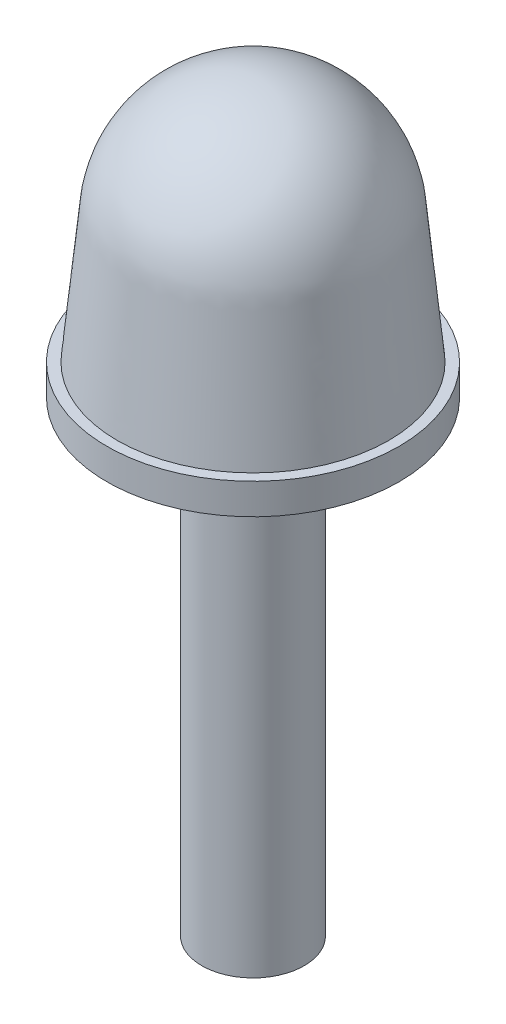
SolidWorks part; units mm, degrees
ref_plane "Front Plane" through (0, 0, 0) normal (0, 0, 1) x (1, 0, 0)
ref_plane "Top Plane" through (0, 0, 0) normal (0, 1, 0) x (1, 0, 0)
ref_plane "Right Plane" through (0, 0, 0) normal (1, 0, 0) x (0, 0, -1)
sketch "Sketch1" plane through (0, 0, 0) normal (0, 0, 1) x (1, 0, 0)
  line L0 (0, 0) -> (0, -72.5)
  line L1 (11.9413, -10.8148) -> (13.25, -24) construction
  line L2 (13.25, -24) -> (14.25, -24)
  line L3 (14.25, -24) -> (14.25, -27)
  line L4 (14.25, -27) -> (9, -27)
  line L5 (9, -27) -> (9, -30)
  line L6 (9, -30) -> (5, -30)
  line L7 (5, -30) -> (5, -72.5)
  line L8 (5, -72.5) -> (0, -72.5)
  arc A0 (0, 0) -> (11.9413, -10.8148) centre (0, -12) cw construction
  spline S0 degree 3 poles (13.25, -24) (12.8763, -20.2348) (12.5026, -16.4695) (12.1289, -12.7043) (12.108, -12.4944) (12.0664, -12.0745) (12.0038, -11.4446) (11.9622, -11.0247) (11.9413, -10.8148) (11.9136, -10.5354) (11.8581, -9.9768) (11.6666, -9.149) (11.5141, -8.6083) (11.4285, -8.3409) (9.7791, -3.189) (5.4095, 0) (0, 0) knots 0 0 0 0 0.379321 0.379321 0.379321 0.400472 0.421623 0.442773 0.442773 0.442773 0.470915 0.499057 0.527199 0.527199 0.527199 1 1 1 1 weights 1 1 1 1 1 1 1 1 1 1 1 1 1 1 0.871834 0.871834 1
  dimension "D1" = 72.5
  dimension "D2" = 12
  dimension "D3" = 1
  dimension "D4" = 3
  dimension "D5" = 24
  dimension "D6" = 14.25
  dimension "D7" = 9
  dimension "D8" = 3
  dimension "D9" = 5
revolve "Revolve1" add sketch "Sketch1" angle 360 about L0
sketch "Sketch2" plane through (0, 0, 0) normal (0, 0, 1) x (1, 0, 0)
  line L0 (14.25, -24) -> (-14.25, -24) construction
  circle A0 centre (0, -11.75) radius 6.125
  dimension "D1" = 12.25
  dimension "D2" = 12.25
sketch "Sketch3" plane through (0, 0, 0) normal (1, 0, 0) x (0, 0, -1)
  line L0 (0, 0) -> (0, -24) construction
  line L1 (14.25, -24) -> (-14.25, -24) construction
  line L2 (21.544, -24) -> (21.544, 0)
  line L3 (-9.75, -24) -> (-21.544, -24)
  line L4 (-7.25, -21.5) -> (-7.25, 0)
  line L5 (-7.25, 0) -> (-21.544, 0)
  line L6 (-21.544, -24) -> (-21.544, 0)
  line L7 (7.25, 0) -> (21.544, 0)
  line L8 (7.25, -21.5) -> (7.25, 0)
  line L9 (9.75, -24) -> (21.544, -24)
  arc A0 (-9.75, -24) -> (-7.25, -21.5) centre (-9.75, -21.5) ccw
  arc A1 (9.75, -24) -> (7.25, -21.5) centre (9.75, -21.5) cw
  point P11 (-7.25, -24)
  point P18 (7.25, -24)
  dimension "D2" = 2.5
  dimension "D1" = 14.5
